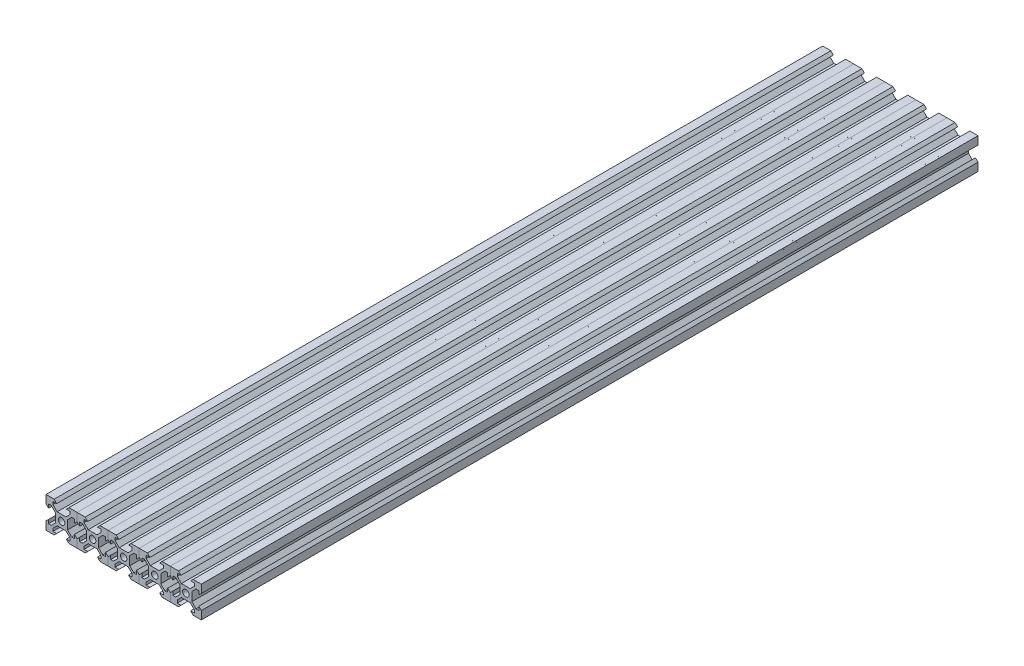
SolidWorks part; units mm, degrees
material "6061-T6 (SS)"
ref_plane "Front Plane" through (0, 0, 0) normal (0, 0, 1) x (1, 0, 0)
ref_plane "Top Plane" through (0, 0, 0) normal (0, 1, 0) x (1, 0, 0)
ref_plane "Right Plane" through (0, 0, 0) normal (1, 0, 0) x (0, 0, -1)
sketch "Sketch1" plane through (0, 0, 0) normal (0, 0, 1) x (1, 0, 0)
  line L0 (2.8343, 3.894) -> (5.5, 6.5588)
  line L1 (2.8343, -3.894) -> (-2.8343, -3.894)
  line L2 (3.8948, -2.8332) -> (3.8948, 2.8332)
  line L3 (2.8343, 3.894) -> (-2.8343, 3.894)
  line L4 (-3.8948, -2.8332) -> (-3.8948, 2.8332)
  line L5 (3.8994, -3.9006) -> (-3.8994, 3.9006) construction
  line L6 (3.9006, 3.8994) -> (-3.9006, -3.8994) construction
  line L7 (10, 4.747) -> (10, 9.9986)
  line L8 (5.5, 6.5588) -> (5.5, 8.3491)
  line L9 (5.5, 8.3491) -> (3.1, 8.3491)
  line L10 (3.1, 8.3491) -> (4.75, 9.9986)
  line L11 (4.75, 9.9986) -> (10, 9.9986)
  line L12 (8.35, 3.0975) -> (10, 4.747)
  line L13 (8.3507, 5.4975) -> (8.35, 3.0975)
  line L14 (6.5605, 5.498) -> (8.3507, 5.4975)
  line L15 (3.8948, 2.8332) -> (6.5605, 5.498)
  line L16 (0, -55) -> (0, 55) construction
  line L17 (-3.8948, 2.8332) -> (-6.5605, 5.498)
  line L18 (-6.5605, 5.498) -> (-8.3507, 5.4975)
  line L19 (-8.3507, 5.4975) -> (-8.35, 3.0975)
  line L20 (-8.35, 3.0975) -> (-10, 4.747)
  line L21 (-4.75, 9.9986) -> (-10, 9.9986)
  line L22 (-3.1, 8.3491) -> (-4.75, 9.9986)
  line L23 (-5.5, 8.3491) -> (-3.1, 8.3491)
  line L24 (-5.5, 6.5588) -> (-5.5, 8.3491)
  line L25 (-10, 4.747) -> (-10, 9.9986)
  line L26 (-2.8343, 3.894) -> (-5.5, 6.5588)
  line L27 (55, 0) -> (-55, 0) construction
  line L28 (3.8948, -2.8332) -> (6.5605, -5.498)
  line L29 (2.8343, -3.894) -> (5.5, -6.5588)
  line L30 (-3.8948, -2.8332) -> (-6.5605, -5.498)
  line L31 (-2.8343, -3.894) -> (-5.5, -6.5588)
  line L32 (-8.3507, -5.4975) -> (-8.35, -3.0975)
  line L33 (-8.35, -3.0975) -> (-10, -4.747)
  line L34 (8.3507, -5.4975) -> (8.35, -3.0975)
  line L35 (8.35, -3.0975) -> (10, -4.747)
  line L36 (-10, -4.747) -> (-10, -9.9986)
  line L37 (-5.5, -6.5588) -> (-5.5, -8.3491)
  line L38 (-5.5, -8.3491) -> (-3.1, -8.3491)
  line L39 (-3.1, -8.3491) -> (-4.75, -9.9986)
  line L40 (-4.75, -9.9986) -> (-10, -9.9986)
  line L41 (-6.5605, -5.498) -> (-8.3507, -5.4975)
  line L42 (6.5605, -5.498) -> (8.3507, -5.4975)
  line L43 (4.75, -9.9986) -> (10, -9.9986)
  line L44 (3.1, -8.3491) -> (4.75, -9.9986)
  line L45 (5.5, -8.3491) -> (3.1, -8.3491)
  line L46 (5.5, -6.5588) -> (5.5, -8.3491)
  line L47 (10, -4.747) -> (10, -9.9986)
  circle A0 centre (0, 0) radius 2.1
  point P0 (0, 0)
  dimension "D6" = 4.2
  dimension "D1" = 7.8
  dimension "D2" = 20
  dimension "D3" = 11
  dimension "D4" = 9.5
  dimension "D5" = 6.2
  dimension "D7" = 1.5
extrude "Boss-Extrude1" add sketch "Sketch1" along normal blind 500
pattern_linear "MatrizL1" count 5 spacing 20 along (1, 0, 0) of bodies 101
